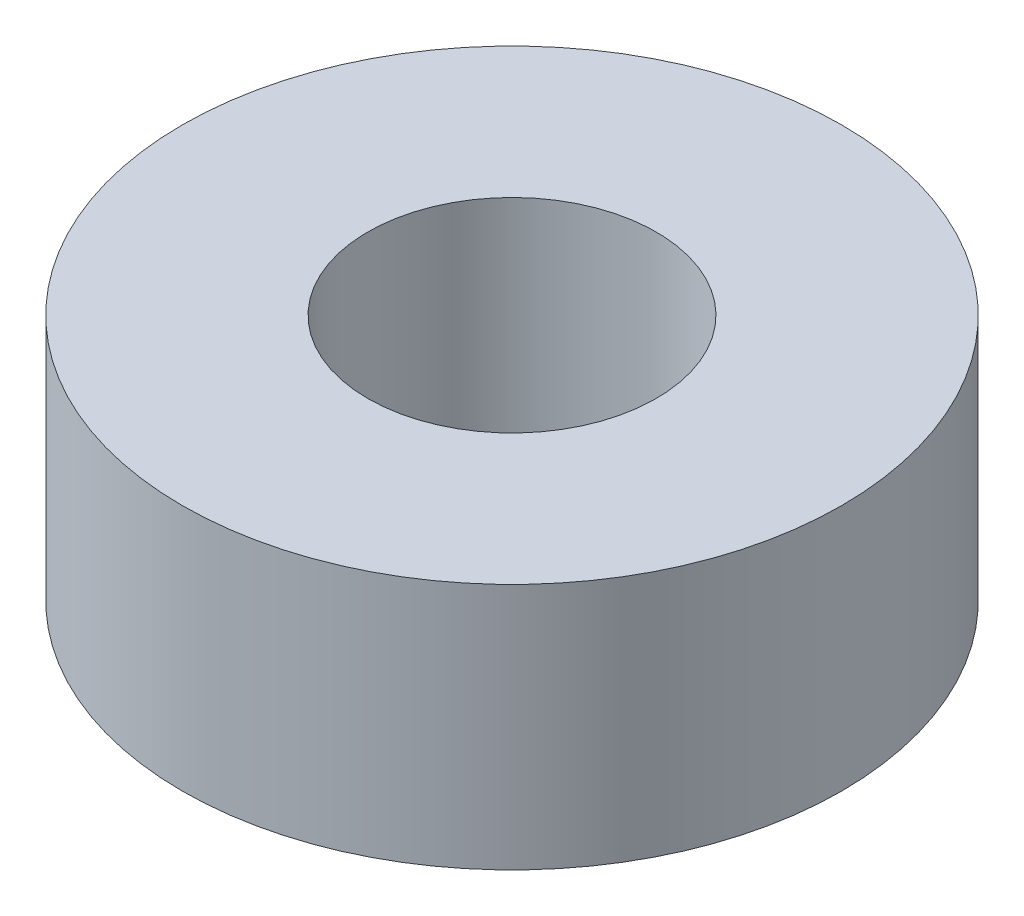
SolidWorks part; units mm, degrees
ref_plane "Спереди" through (0, 0, 0) normal (0, 0, 1) x (1, 0, 0)
ref_plane "Сверху" through (0, 0, 0) normal (0, 1, 0) x (1, 0, 0)
ref_plane "Справа" through (0, 0, 0) normal (1, 0, 0) x (0, 0, -1)
sketch "Эскиз1" plane through (0, 0, 0) normal (0, 1, 0) x (1, 0, 0)
  circle A0 centre (0, 0) radius 4
  circle A1 centre (0, 0) radius 1.75
  dimension "D1" = 8
  dimension "D2" = 3.5
extrude "Бобышка-Вытянуть1" add sketch "Эскиз1" along normal blind 3
